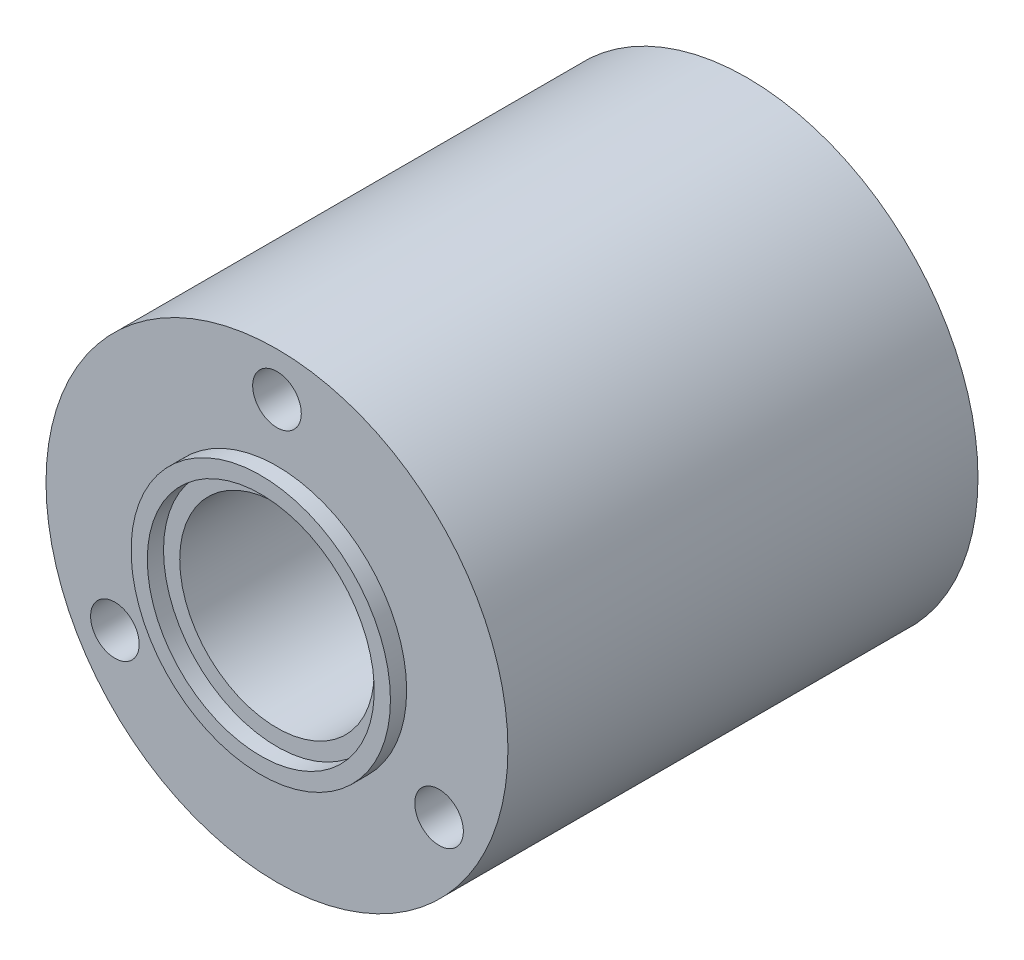
SolidWorks part; units mm, degrees
ref_plane "Front Plane" through (0, 0, 0) normal (0, 0, 1) x (1, 0, 0)
ref_plane "Top Plane" through (0, 0, 0) normal (0, 1, 0) x (1, 0, 0)
ref_plane "Right Plane" through (0, 0, 0) normal (1, 0, 0) x (0, 0, -1)
sketch "Sketch1" plane through (0, 0, 0) normal (0, 0, 1) x (1, 0, 0)
  circle A0 centre (0, 0) radius 7
  circle A1 centre (0, 0) radius 14.25
  dimension "D1" = 14
  dimension "D2" = 28.5
extrude "Boss-Extrude1" add sketch "Sketch1" along normal blind 29
sketch "Sketch2" plane through (0, 0, 29) normal (0, 0, 1) x (1, 0, 0)
  circle A0 centre (0, 0) radius 7
  circle A1 centre (0, 0) radius 8
  circle A2 centre (0, 0) radius 7 construction
  dimension "D1" = 1
extrude "Boss-Extrude2" add sketch "Sketch2" along normal blind 1
ref_plane "Plane1" through (0, 0, 14.5) normal (0, 0, 1) x (1, 0, 0)
mirror "Mirror1" about plane through (0, 0, 14.5) normal (0, 0, 1) of "Boss-Extrude2"
sketch "Sketch3" plane through (0, 0, 29) normal (0, 0, 1) x (1, 0, 0)
  line L0 (0, 0) -> (0, 14.25) construction
  circle A0 centre (0, 11.547) radius 1.5
  circle A1 centre (10, -5.7735) radius 1.5
  circle A2 centre (-10, -5.7735) radius 1.5
  circle A3 centre (0, 0) radius 14.25 construction
  point P9 (0, 0)
  dimension "D1" = 3
  dimension "D2" = 20
  dimension "D3" = 3
extrude "Cut-Extrude1" cut sketch "Sketch3" against normal through all
sketch "Sketch4" plane through (0, 0, 29) normal (0, 0, 1) x (1, 0, 0)
  circle A0 centre (0, 0) radius 7
  circle A1 centre (0, 0) radius 6
  dimension "D1" = 14
  dimension "D2" = 12
extrude "Boss-Extrude3" add sketch "Sketch4" against normal blind 29
